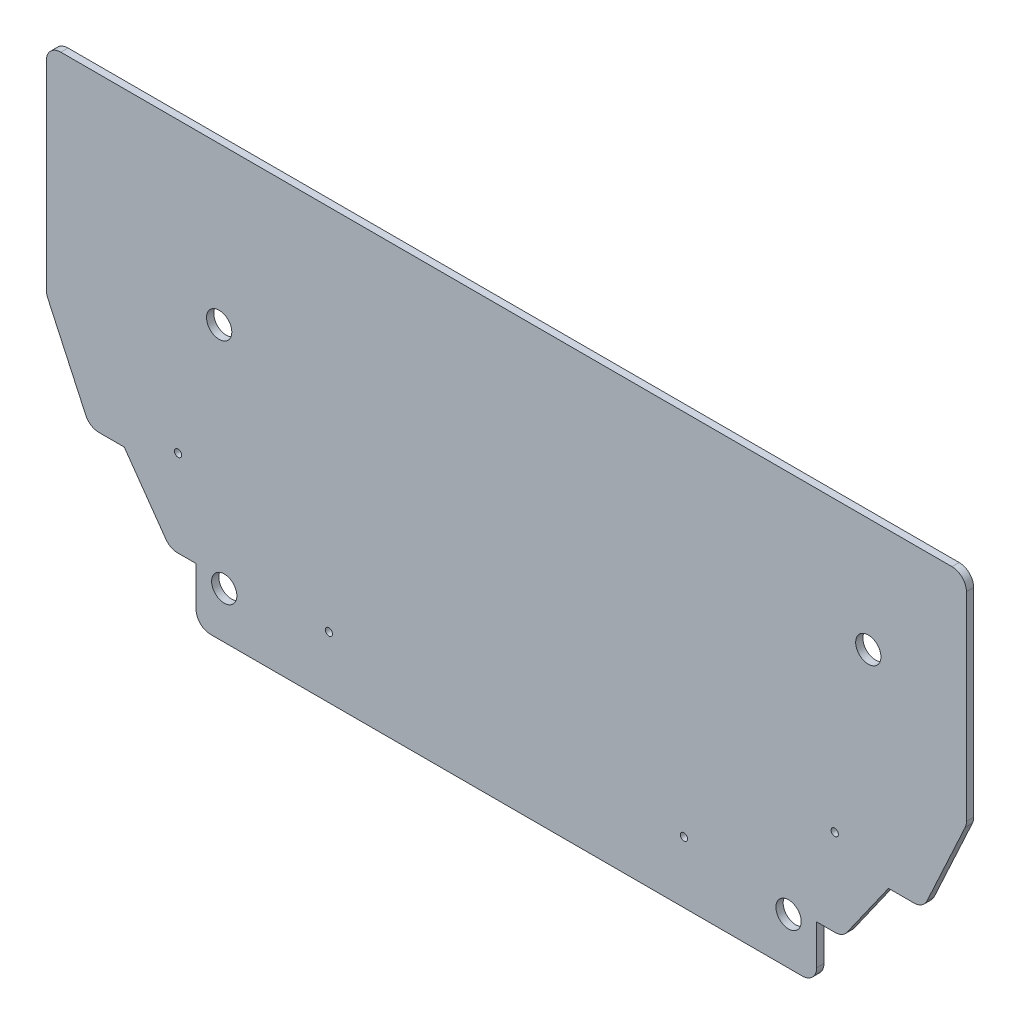
SolidWorks part; units mm, degrees
ref_plane "Plan de face" through (0, 0, 0) normal (0, 0, 1) x (1, 0, 0)
ref_plane "Plan de dessus" through (0, 0, 0) normal (0, 1, 0) x (1, 0, 0)
ref_plane "Plan de droite" through (0, 0, 0) normal (1, 0, 0) x (0, 0, -1)
sketch "Esquisse1" plane through (0, 0, 0) normal (0, 0, 1) x (1, 0, 0)
  line L1 (0, 0) -> (127.5, 0)
  line L2 (0, 0) -> (0, 59.5)
  line L3 (0, 59.5) -> (127.5, 59.5)
  line L4 (127.5, 0) -> (127.5, 59.5)
  dimension "D1" = 127.5
  dimension "D2" = 59.5
extrude "Boss.-Extru.1" add sketch "Esquisse1" along normal blind 1
sketch "Esquisse3" plane through (0, 0, 1) normal (0, 0, 1) x (1, 0, 0)
  line L0 (127.5, 29.5) -> (121.5, 16.5)
  line L1 (127.5, 0) -> (127.5, 59.5) construction
  line L2 (121.5, 16.5) -> (116.7, 16.5)
  line L3 (116.7, 16.5) -> (110.35, 7.5)
  line L4 (110.35, 7.5) -> (106.75, 7.5)
  line L5 (106.75, 7.5) -> (106.75, 0)
  line L6 (0, 0) -> (127.5, 0) construction
  line L7 (127.5, 59.5) -> (0, 59.5) construction
  line L8 (63.75, 0) -> (63.75, 59.5) construction
  line L9 (127.5, 29.5) -> (127.5, 0)
  line L10 (127.5, 0) -> (106.75, 0)
  line L11 (0, 0) -> (20.75, 0)
  line L12 (0, 29.5) -> (0, 0)
  line L13 (20.75, 7.5) -> (20.75, 0)
  line L14 (17.15, 7.5) -> (20.75, 7.5)
  line L15 (10.8, 16.5) -> (17.15, 7.5)
  line L16 (6, 16.5) -> (10.8, 16.5)
  line L17 (0, 29.5) -> (6, 16.5)
  line L18 (0, 59.5) -> (0, 0) construction
  circle A0 centre (102.85, 6.45) radius 1.75
  circle A1 centre (113.9, 43.75) radius 1.75
  circle A2 centre (23.95, 37.75) radius 1.75
  circle A3 centre (24.65, 6.45) radius 1.75
  dimension "D9" = 3.5
  dimension "D1" = 30
  dimension "D2" = 43
  dimension "D3" = 52
  dimension "D4" = 6
  dimension "D5" = 10.8
  dimension "D6" = 20.75
  dimension "D7" = 3.6
  dimension "D8" = 6.45
  dimension "D10" = 86
  dimension "D11" = 3.9
  dimension "D12" = 13.6
  dimension "D13" = 15.75
  dimension "D14" = 21.75
  dimension "D15" = 23.95
  dimension "D16" = 3.9
extrude "Enlèv. mat.-Extru.1" cut sketch "Esquisse3" against normal through all
sketch "Esquisse5" plane through (0, 0, 1) normal (0, 0, 1) x (1, 0, 0)
  line L0 (39.15, 8.5) -> (88.35, 8.5) construction
  line L1 (63.75, 8.5) -> (63.75, 0) construction
  line L2 (20.75, 0) -> (106.75, 0) construction
  line L3 (18.25, 19.5) -> (109.25, 19.5) construction
  line L4 (63.75, 19.5) -> (63.75, 8.5) construction
  circle A0 centre (39.15, 8.5) radius 0.5
  circle A1 centre (88.35, 8.5) radius 0.5
  circle A2 centre (109.25, 19.5) radius 0.5
  circle A3 centre (18.25, 19.5) radius 0.5
  dimension "D1" = 1
  dimension "D2" = 49.2
  dimension "D3" = 8.5
  dimension "D4" = 91
  dimension "D5" = 19.5
extrude "Enlèv. mat.-Extru.3" cut sketch "Esquisse5" against normal through all
sketch "Esquisse4" plane through (0, 0, 1) normal (0, 0, 1) x (1, 0, 0)
  line L0 (127.5, 59.5) -> (0, 59.5) construction
  line L1 (23.25, 59.5) -> (104.25, 59.5) construction
  line L2 (36.4946, 44.6) -> (89.3262, 44.6) construction
  line L3 (20.75, 0) -> (106.75, 0) construction
  arc A0 (23.25, 59.5) -> (104.25, 59.5) centre (63.75, 107.0919) ccw construction
  circle A1 centre (54.9869, 53.198) radius 0.9584
  point P3 (63.75, 59.5)
  dimension "D1" = 81
  dimension "D2" = 44.6
extrude "Enlèv. mat.-Extru.2" [suppressed] cut sketch "Esquisse4" against normal through all
fillet "Congé1" radius 2 10 edges at (106.75, 0, 0.5) (20.75, 0, 0.5) (127.5, 59.5, 0.5) (0, 59.5, 0.5) (110.35, 7.5, 0.5) (121.5, 16.5, 0.5) (127.5, 29.5, 0.5) (17.15, 7.5, 0.5) (6, 16.5, 0.5) (0, 29.5, 0.5)
